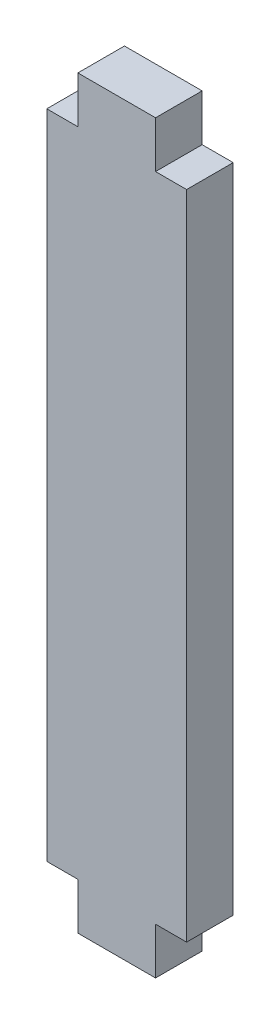
SolidWorks part; units mm, degrees
ref_plane "Front Plane" through (0, 0, 0) normal (0, 0, 1) x (1, 0, 0)
ref_plane "Top Plane" through (0, 0, 0) normal (0, 1, 0) x (1, 0, 0)
ref_plane "Right Plane" through (0, 0, 0) normal (1, 0, 0) x (0, 0, -1)
sketch "Sketch1" plane through (0, 0, 0) normal (0, 0, 1) x (1, 0, 0)
  line L0 (0, 0) -> (4.5, 0) construction
  line L1 (4.5, -20.975) -> (-4.5, -20.975)
  line L2 (4.5, -20.975) -> (4.5, 20.975)
  line L3 (4.5, 20.975) -> (-4.5, 20.975)
  line L4 (-4.5, -20.975) -> (-4.5, 20.975)
  line L5 (4.5, -20.975) -> (-4.5, 20.975) construction
  line L6 (4.5, 20.975) -> (-4.5, -20.975) construction
  line L7 (2.5, -20.975) -> (-2.5, -20.975)
  line L8 (2.5, 23.975) -> (-2.5, 23.975)
  line L9 (2.5, 23.975) -> (2.5, 20.975)
  line L10 (2.5, 20.975) -> (-2.5, 20.975)
  line L11 (-2.5, 23.975) -> (-2.5, 20.975)
  line L12 (2.5, 23.975) -> (-2.5, 20.975) construction
  line L13 (2.5, 20.975) -> (-2.5, 23.975) construction
  line L14 (-2.5, -23.975) -> (-2.5, -20.975)
  line L15 (2.5, -23.975) -> (-2.5, -23.975)
  line L16 (2.5, -23.975) -> (2.5, -20.975)
  point P0 (0, 0)
  point P8 (0, 22.475)
  point P13 (0, 0)
  point P14 (0, 20.975)
  dimension "D1" = 9
  dimension "D2" = 41.95
  dimension "D3" = 5
  dimension "D4" = 3
extrude "Boss-Extrude1" add sketch "Sketch1" along normal blind 3 contours L4 L1 L2 L3 | L15 L16 L1 L14 | L9 L10 L11 L8
